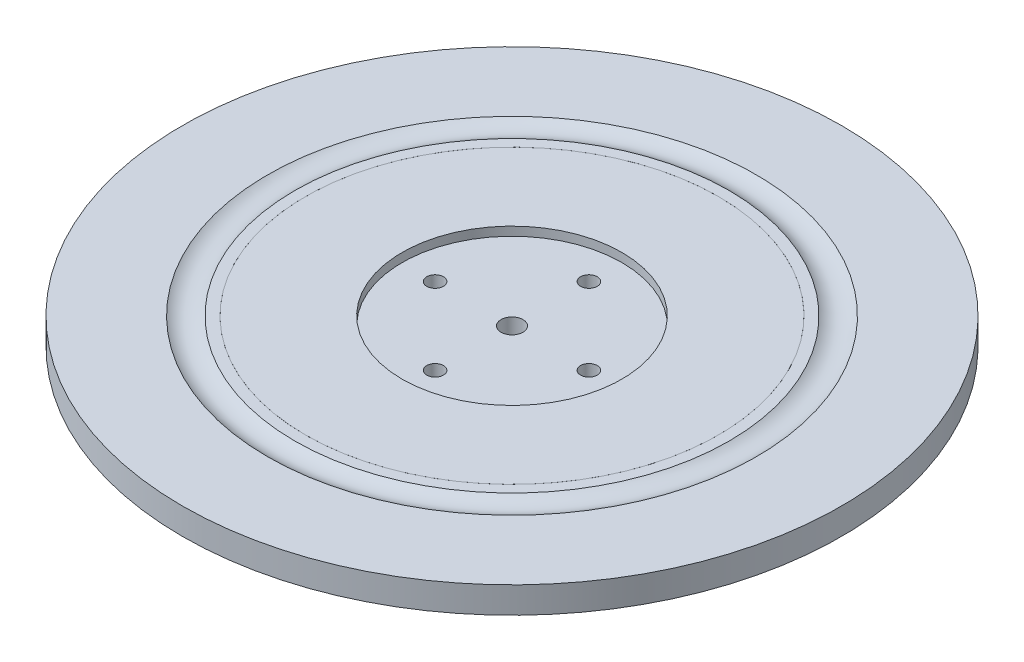
SolidWorks part; units mm, degrees
ref_plane "Front Plane" through (0, 0, 0) normal (0, 0, 1) x (1, 0, 0)
ref_plane "Top Plane" through (0, 0, 0) normal (0, 1, 0) x (1, 0, 0)
ref_plane "Right Plane" through (0, 0, 0) normal (1, 0, 0) x (0, 0, -1)
ref_plane "Plane1" through (0, 0, 0) normal (0, 0, -1) x (-1, 0, 0)
sketch "Sketch1" plane through (0, 0, 0) normal (0, 0, -1) x (-1, 0, 0)
  line L0 (-59, 0.8724) -> (-47, 0.8724)
  line L1 (-46, 1.8724) -> (-46, 5.8724)
  line L2 (-46, 5.8724) -> (-47, 6.8724)
  line L3 (-47, 6.8724) -> (-49.4043, 6.8724)
  line L4 (-55.5957, 6.8724) -> (-59, 6.8724)
  line L5 (-59, 6.8724) -> (-60, 5.8724)
  line L6 (-60, 5.8724) -> (-60, 1.8724)
  line L7 (0, 0) -> (0, 6.8724) construction
  arc A0 (-47, 0.8724) -> (-46, 1.8724) centre (-47, 1.8724) ccw
  arc A1 (-49.4043, 6.8724) -> (-55.5957, 6.8724) centre (-52.5, 11) cw
  arc A2 (-60, 1.8724) -> (-59, 0.8724) centre (-59, 1.8724) ccw
  dimension "D1" = 5.1595
  dimension "D2" = 14
  dimension "D3" = 6.1914
  dimension "D4" = 6
revolve "Revolve1" add sketch "Sketch1" angle 360 about L7
sketch "Sketch2" plane through (0, 0.8724, 0) normal (0, -1, 0) x (1, 0, 0)
  circle A0 centre (0, 0) radius 75
  circle A2 centre (0, 0) radius 46.9929
  circle A3 centre (0, 0) radius 59
extrude "Boss-Extrude1" add sketch "Sketch2" against normal blind 6 contours A0 A3 | A2
sketch "Sketch4" plane through (0, 0.8724, 0) normal (0, -1, 0) x (1, 0, 0)
  circle A0 centre (0, 0) radius 2.5
extrude "Cut-Extrude1" cut sketch "Sketch4" against normal blind 8
sketch "Sketch5" plane through (0, 0.8724, 0) normal (0, -1, 0) x (1, 0, 0)
  circle A0 centre (0, 0) radius 21 construction
  circle A4 centre (0, 0) radius 17.5 construction
  circle A5 centre (0, 17.5) radius 1.9
  circle A6 centre (17.5, 0) radius 1.9
  circle A7 centre (0, -17.5) radius 1.9
  circle A8 centre (-17.5, 0) radius 1.9
  point P12 (0, 0)
  point P16 (0, 0)
  dimension "D1" = 42
  dimension "D2" = 3.8
  dimension "D3" = 4
extrude "Cut-Extrude2" cut sketch "Sketch5" against normal blind 8
sketch "Sketch7" plane through (0, 0.8724, 0) normal (0, -1, 0) x (1, 0, 0)
  circle A1 centre (0, 0) radius 15
extrude "Cut-Extrude3" [suppressed] cut sketch "Sketch7" against normal blind 3
sketch "Sketch8" plane through (0, 6.8724, 0) normal (0, 1, 0) x (1, 0, 0)
  circle A0 centre (0, 0) radius 25
extrude "Cut-Extrude4" cut sketch "Sketch8" against normal blind 2
